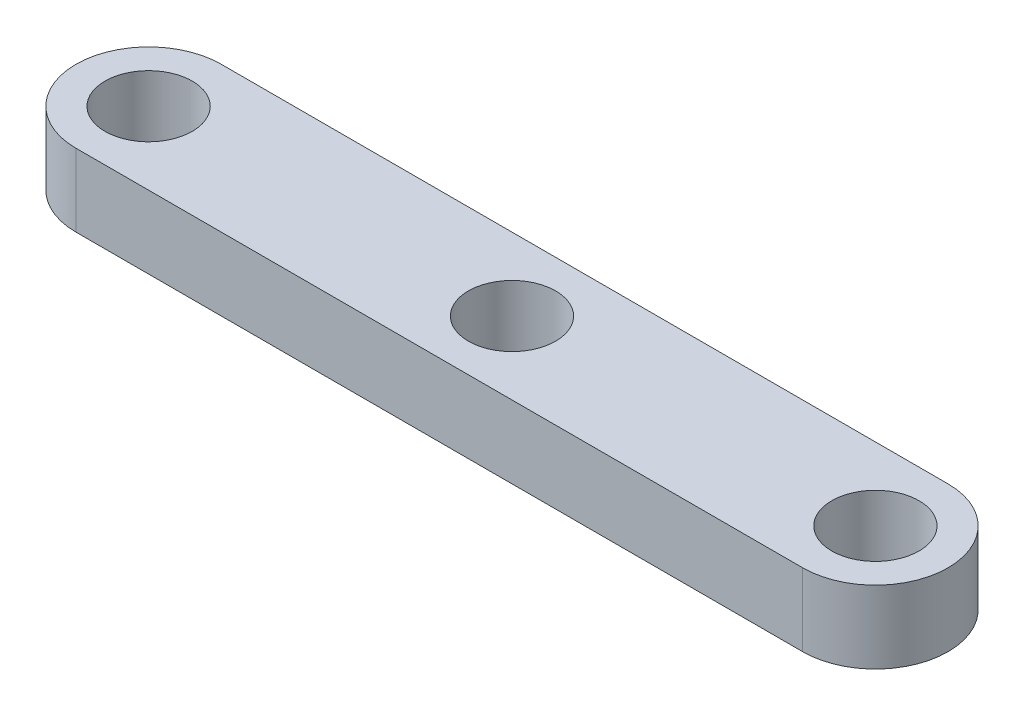
SolidWorks part; units mm, degrees
ref_plane "Front Plane" through (0, 0, 0) normal (0, 0, 1) x (1, 0, 0)
ref_plane "Top Plane" through (0, 0, 0) normal (0, 1, 0) x (1, 0, 0)
ref_plane "Right Plane" through (0, 0, 0) normal (1, 0, 0) x (0, 0, -1)
sketch "Sketch1" plane through (0, 0, 0) normal (0, 1, 0) x (1, 0, 0)
  line L0 (-55, 0) -> (55, 0) construction
  line L1 (-12.7, 2.54) -> (12.7, 2.54)
  line L2 (-12.7, -2.54) -> (12.7, -2.54)
  circle A0 centre (0, 0) radius 1.524
  circle A1 centre (-12.7, 0) radius 1.524
  circle A2 centre (12.7, 0) radius 1.524
  arc A3 (-12.7, 2.54) -> (-12.7, -2.54) centre (-12.7, 0) ccw
  arc A5 (12.7, -2.54) -> (12.7, 2.54) centre (12.7, 0) ccw
  dimension "D3" = 3.048
  dimension "D4" = 5.08
  dimension "D1" = 12.7
  dimension "D2" = 12.7
extrude "Boss-Extrude1" add sketch "Sketch1" along normal blind 2.54
